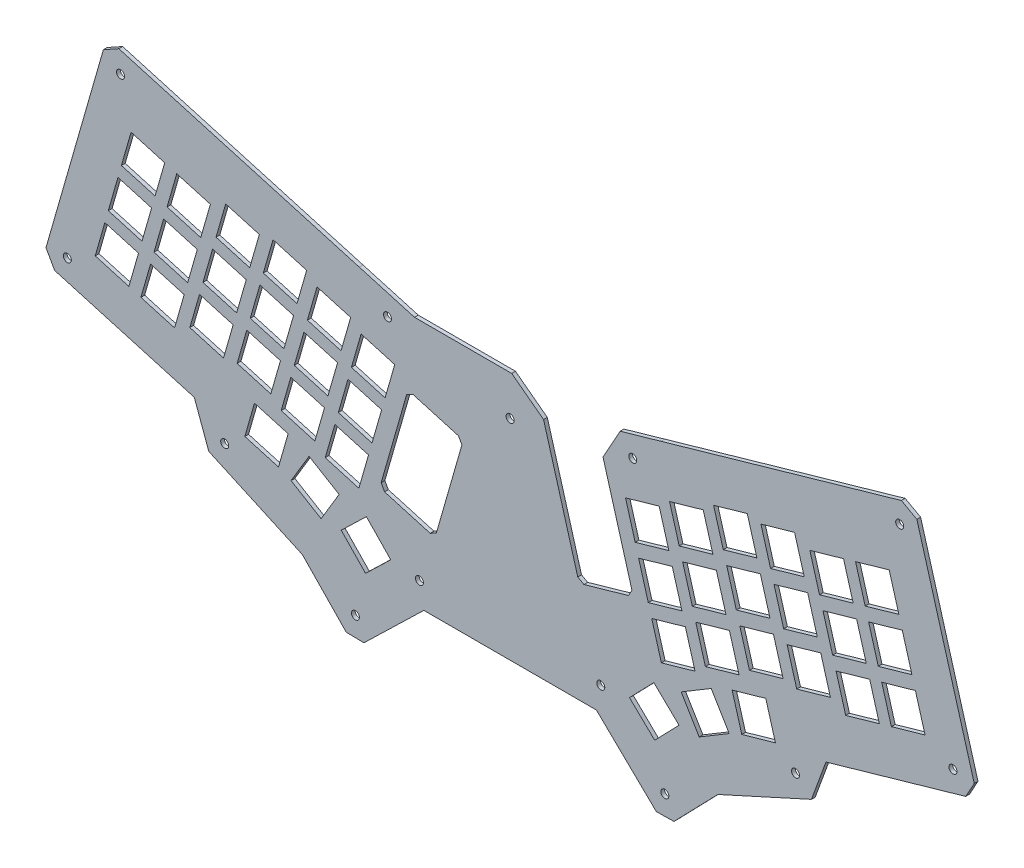
SolidWorks part; units mm, degrees
ref_plane "Plan de face" through (0, 0, 0) normal (0, 0, 1) x (1, 0, 0)
ref_plane "Plan de dessus" through (0, 0, 0) normal (0, 1, 0) x (1, 0, 0)
ref_plane "Plan de droite" through (0, 0, 0) normal (1, 0, 0) x (0, 0, -1)
sketch "Esquisse1" plane through (0, 0, 0) normal (0, 0, 1) x (1, 0, 0)
  line L0 (-121.6461, -32.0475) -> (-108.1875, -28.1884)
  line L1 (-108.1875, -28.1884) -> (-104.3283, -41.647)
  line L2 (-104.3283, -41.647) -> (-117.7869, -45.5062)
  line L3 (-117.7869, -45.5062) -> (-121.6461, -32.0475)
  line L4 (-100.1763, -37.9855) -> (-104.0355, -24.5269)
  line L5 (-104.0355, -24.5269) -> (-90.5769, -20.6677)
  line L6 (-90.5769, -20.6677) -> (-86.7177, -34.1263)
  line L7 (-86.7177, -34.1263) -> (-100.1763, -37.9855)
  line L8 (-82.5657, -30.4649) -> (-86.4249, -17.0063)
  line L9 (-86.4249, -17.0063) -> (-72.9663, -13.1471)
  line L10 (-72.9663, -13.1471) -> (-69.1071, -26.6057)
  line L11 (-69.1071, -26.6057) -> (-82.5657, -30.4649)
  line L12 (-63.6458, -27.5106) -> (-67.505, -14.0519)
  line L13 (-67.505, -14.0519) -> (-54.0463, -10.1927)
  line L14 (-54.0463, -10.1927) -> (-50.1872, -23.6514)
  line L15 (-50.1872, -23.6514) -> (-63.6458, -27.5106)
  line L16 (-44.0711, -26.8394) -> (-47.9303, -13.3808)
  line L17 (-47.9303, -13.3808) -> (-34.4717, -9.5216)
  line L18 (-34.4717, -9.5216) -> (-30.6125, -22.9802)
  line L19 (-30.6125, -22.9802) -> (-44.0711, -26.8394)
  line L20 (-25.8054, -21.6018) -> (-29.6646, -8.1432)
  line L21 (-29.6646, -8.1432) -> (-16.206, -4.284)
  line L22 (-16.206, -4.284) -> (-12.3468, -17.7426)
  line L23 (-12.3468, -17.7426) -> (-25.8054, -21.6018)
  line L24 (-116.4086, -50.3128) -> (-102.95, -46.4536)
  line L25 (-102.95, -46.4536) -> (-99.0908, -59.9122)
  line L26 (-99.0908, -59.9122) -> (-112.5494, -63.7714)
  line L27 (-112.5494, -63.7714) -> (-116.4086, -50.3128)
  line L28 (-98.798, -42.7922) -> (-85.3394, -38.933)
  line L29 (-85.3394, -38.933) -> (-81.4802, -52.3916)
  line L30 (-81.4802, -52.3916) -> (-94.9388, -56.2508)
  line L31 (-94.9388, -56.2508) -> (-98.798, -42.7922)
  line L32 (-81.1874, -35.2715) -> (-67.7288, -31.4123)
  line L33 (-67.7288, -31.4123) -> (-63.8696, -44.8709)
  line L34 (-63.8696, -44.8709) -> (-77.3282, -48.7301)
  line L35 (-77.3282, -48.7301) -> (-81.1874, -35.2715)
  line L36 (-62.2675, -32.3172) -> (-48.8089, -28.458)
  line L37 (-48.8089, -28.458) -> (-44.9497, -41.9166)
  line L38 (-44.9497, -41.9166) -> (-58.4083, -45.7758)
  line L39 (-58.4083, -45.7758) -> (-62.2675, -32.3172)
  line L40 (-42.6928, -31.646) -> (-29.2342, -27.7869)
  line L41 (-29.2342, -27.7869) -> (-25.375, -41.2455)
  line L42 (-25.375, -41.2455) -> (-38.8336, -45.1047)
  line L43 (-38.8336, -45.1047) -> (-42.6928, -31.646)
  line L44 (-24.4271, -26.4084) -> (-10.9685, -22.5492)
  line L45 (-10.9685, -22.5492) -> (-7.1093, -36.0078)
  line L46 (-7.1093, -36.0078) -> (-20.5679, -39.867)
  line L47 (-20.5679, -39.867) -> (-24.4271, -26.4084)
  line L48 (-19.1896, -44.6737) -> (-5.731, -40.8145)
  line L49 (-5.731, -40.8145) -> (-1.8718, -54.2731)
  line L50 (-1.8718, -54.2731) -> (-15.3304, -58.1323)
  line L51 (-15.3304, -58.1323) -> (-19.1896, -44.6737)
  line L52 (-37.4554, -49.9113) -> (-23.9967, -46.0521)
  line L53 (-23.9967, -46.0521) -> (-20.1376, -59.5107)
  line L54 (-20.1376, -59.5107) -> (-33.5962, -63.3699)
  line L55 (-33.5962, -63.3699) -> (-37.4554, -49.9113)
  line L56 (-57.03, -50.5825) -> (-43.5714, -46.7233)
  line L57 (-43.5714, -46.7233) -> (-39.7122, -60.1819)
  line L58 (-39.7122, -60.1819) -> (-53.1708, -64.0411)
  line L59 (-53.1708, -64.0411) -> (-57.03, -50.5825)
  line L60 (-75.9499, -53.5368) -> (-62.4913, -49.6776)
  line L61 (-62.4913, -49.6776) -> (-58.6321, -63.1362)
  line L62 (-58.6321, -63.1362) -> (-72.0908, -66.9954)
  line L63 (-72.0908, -66.9954) -> (-75.9499, -53.5368)
  line L64 (-93.5605, -61.0574) -> (-80.1019, -57.1982)
  line L65 (-80.1019, -57.1982) -> (-76.2427, -70.6569)
  line L66 (-76.2427, -70.6569) -> (-89.7013, -74.516)
  line L67 (-89.7013, -74.516) -> (-93.5605, -61.0574)
  line L68 (-111.1711, -68.5781) -> (-97.7125, -64.7189)
  line L69 (-97.7125, -64.7189) -> (-93.8533, -78.1775)
  line L70 (-93.8533, -78.1775) -> (-107.3119, -82.0367)
  line L71 (-107.3119, -82.0367) -> (-111.1711, -68.5781)
  line L72 (-79.0181, -77.3048) -> (-65.5595, -73.4456)
  line L73 (-65.5595, -73.4456) -> (-61.7003, -86.9042)
  line L74 (-61.7003, -86.9042) -> (-75.1589, -90.7634)
  line L75 (-75.1589, -90.7634) -> (-79.0181, -77.3048)
  line L76 (-99.4001, -88.1351) -> (-87.3916, -80.9362)
  line L77 (-87.3916, -80.9362) -> (-80.1927, -92.9448)
  line L78 (-80.1927, -92.9448) -> (-92.2012, -100.1436)
  line L79 (-92.2012, -100.1436) -> (-99.4001, -88.1351)
  line L80 (-120.0498, -100.4367) -> (-110.317, -90.3719)
  line L81 (-110.317, -90.3719) -> (-100.2522, -100.1047)
  line L82 (-100.2522, -100.1047) -> (-109.985, -110.1695)
  line L83 (-109.985, -110.1695) -> (-120.0498, -100.4367)
  line L86 (0.634, -55.7756) -> (-52.9527, -71.1413) construction
  line L89 (-59.2205, -88.2424) -> (-52.9527, -71.1413) construction
  line L96 (-93.4066, -103.0586) -> (-59.4637, -88.3612) construction
  line L97 (-105.418, -115.2057) -> (-93.9754, -103.3509) construction
  line L98 (-126.5332, -96.9919) -> (-107.5003, -115.385) construction
  line L100 (-106.3822, -25.4572) -> (-123.6848, -30.4187) construction
  line L101 (-72.1178, -10.6906) -> (-88.4663, -15.3784) construction
  line L102 (-53.2337, -7.6163) -> (-70.5393, -12.5786) construction
  line L103 (-33.6604, -6.9452) -> (-50.9661, -11.9075) construction
  line L104 (-15.3965, -1.7081) -> (-31.745, -6.396) construction
  line L105 (0.5403, -55.2132) -> (-14.6896, -2.0999) construction
  line L106 (-16.199, -60.6113) -> (0.1495, -55.9235) construction
  line L107 (-52.7198, -71.0835) -> (-18.1144, -61.1606) construction
  line L108 (-59.1184, -88.0534) -> (-52.9674, -71.2752) construction
  line L113 (-102.2678, -134.438) -> (-84.7238, -116.3191)
  line L114 (-84.7238, -116.3191) -> (-47.2969, -99.2981)
  line L115 (-47.2969, -99.2981) -> (-41.4917, -83.4594)
  line L116 (14.3812, -67.4381) -> (-41.4917, -83.4594)
  line L117 (17.8093, -61.2536) -> (-5.1371, 18.7701)
  line L122 (-11.3217, 22.1985) -> (-107.4545, -5.3614)
  line L129 (-167.7953, -27.6055) -> (-167.7953, -64.7189) construction
  line L130 (-242.0685, -103.8419) -> (-276.37, -88.2424) construction
  line L131 (-229.5108, -116.8112) -> (-242.0685, -103.8419) construction
  line L138 (-208.9328, -96.8551) -> (-229.5108, -116.8112) construction
  line L139 (-225.5107, -79.6567) -> (-208.9328, -96.8551) construction
  line L140 (-109.3352, -134.5492) -> (-102.2678, -134.438)
  line L142 (-5.1371, 18.7701) -> (-11.3217, 22.1985)
  line L143 (-211.4691, -30.6868) -> (-225.5107, -79.6567) construction
  line L147 (-114.18, -7.2899) -> (-107.4545, -5.3614)
  line L148 (-114.18, -7.2899) -> (-123.7936, -10.0465)
  line L154 (-4.3102, 15.8863) -> (-127.3606, -19.3904) construction
  line L155 (-131.531, -101.8802) -> (-105.9239, -126.7133) construction
  line L156 (-105.9239, -126.7133) -> (-89.4162, -109.6646) construction
  line L157 (-127.3539, -97.573) -> (-106.0575, -118.2258) construction
  line L158 (-106.0575, -118.2258) -> (-92.9354, -104.6737) construction
  line L159 (-92.9354, -104.6737) -> (-58.4256, -88.9794) construction
  line L160 (-58.4256, -88.9794) -> (-52.1886, -71.9625) construction
  line L161 (1.8709, -56.4612) -> (-52.1886, -71.9625) construction
  line L162 (1.8709, -56.4612) -> (-14.1861, -0.4639) construction
  line L163 (-14.1861, -0.4639) -> (-50.7166, -10.9388) construction
  line L164 (-50.7166, -10.9388) -> (-52.026, -6.3725) construction
  line L165 (-52.026, -6.3725) -> (-70.2913, -11.61) construction
  line L166 (-70.2913, -11.61) -> (-70.911, -9.4488) construction
  line L167 (-70.911, -9.4488) -> (-90.1377, -14.9608) construction
  line L168 (-90.1377, -14.9608) -> (-89.5177, -17.1231) construction
  line L169 (-89.5177, -17.1231) -> (-107.783, -22.3606) construction
  line L170 (-107.783, -22.3606) -> (-107.0938, -24.7639) construction
  line L171 (-107.0938, -24.7639) -> (-125.3583, -30.0011) construction
  line L172 (-125.3583, -30.0011) -> (-111.0411, -79.9324) construction
  line L173 (-110.7998, -78.9627) -> (-127.3777, -96.1611) construction
  line L174 (-89.4162, -109.6646) -> (-53.6562, -93.4017) construction
  line L175 (-53.6562, -93.4017) -> (-47.6042, -76.8897) construction
  line L176 (9.2923, -60.5749) -> (-47.6042, -76.8897) construction
  line L177 (9.2923, -60.5749) -> (-12.0005, 13.6817) construction
  line L178 (-229.7336, -25.4495) -> (-211.4691, -30.6868) construction
  line L179 (-229.0444, -23.0462) -> (-229.7336, -25.4495) construction
  line L181 (-247.3097, -17.8087) -> (-229.0444, -23.0462) construction
  line L185 (17.8093, -61.2536) -> (14.3812, -67.4381)
  line L190 (-246.6897, -15.6465) -> (-247.3097, -17.8087) construction
  line L191 (-263.9939, -10.6857) -> (-246.6897, -15.6465) construction
  line L192 (-264.6136, -12.8469) -> (-263.9939, -10.6857) construction
  line L193 (-282.8789, -7.6094) -> (-264.6136, -12.8469) construction
  line L194 (-284.1883, -12.1757) -> (-282.8789, -7.6094) construction
  line L195 (-320.7188, -1.7008) -> (-284.1883, -12.1757) construction
  line L196 (-336.2245, -55.7756) -> (-320.7188, -1.7008) construction
  line L200 (-344.8828, -60.5749) -> (-323.5901, 13.6817) construction
  line L201 (-344.8828, -60.5749) -> (-287.9863, -76.8897) construction
  line L202 (-281.9343, -93.4017) -> (-287.9863, -76.8897) construction
  line L203 (-246.1743, -109.6646) -> (-281.9343, -93.4017) construction
  line L204 (-224.7907, -78.9627) -> (-208.2128, -96.1611) construction
  line L205 (-210.2322, -30.0011) -> (-224.5494, -79.9324) construction
  line L206 (-228.4967, -24.7639) -> (-210.2322, -30.0011) construction
  line L207 (-227.8075, -22.3606) -> (-228.4967, -24.7639) construction
  line L208 (-246.0728, -17.1231) -> (-227.8075, -22.3606) construction
  line L209 (-245.4528, -14.9608) -> (-246.0728, -17.1231) construction
  line L210 (-264.6796, -9.4488) -> (-245.4528, -14.9608) construction
  line L211 (-265.2993, -11.61) -> (-264.6796, -9.4488) construction
  line L212 (-283.5645, -6.3725) -> (-265.2993, -11.61) construction
  line L213 (-284.8739, -10.9388) -> (-283.5645, -6.3725) construction
  line L217 (0.634, -55.7756) -> (-14.8717, -1.7008) construction
  line L220 (-14.8717, -1.7008) -> (-51.4022, -12.1757) construction
  line L221 (-51.4022, -12.1757) -> (-52.7116, -7.6094) construction
  line L222 (-52.7116, -7.6094) -> (-70.9769, -12.8469) construction
  line L223 (-70.9769, -12.8469) -> (-71.5966, -10.6857) construction
  line L224 (-71.5966, -10.6857) -> (-88.9008, -15.6465) construction
  line L225 (-88.9008, -15.6465) -> (-88.2808, -17.8087) construction
  line L226 (-88.2808, -17.8087) -> (-106.5461, -23.0462) construction
  line L227 (-106.5461, -23.0462) -> (-105.8569, -25.4495) construction
  line L228 (-105.8569, -25.4495) -> (-124.1214, -30.6868) construction
  line L231 (-124.1214, -30.6868) -> (-110.0799, -79.6567) construction
  line L232 (-110.0799, -79.6567) -> (-126.6577, -96.8551) construction
  line L233 (-126.6577, -96.8551) -> (-106.0797, -116.8112) construction
  line L234 (-106.0797, -116.8112) -> (-93.522, -103.8419) construction
  line L235 (-93.522, -103.8419) -> (-59.2205, -88.2424) construction
  line L236 (-321.4044, -0.4639) -> (-284.8739, -10.9388) construction
  line L237 (-337.4614, -56.4612) -> (-321.4044, -0.4639) construction
  line L238 (-337.4614, -56.4612) -> (-283.4019, -71.9625) construction
  line L239 (-277.1649, -88.9794) -> (-283.4019, -71.9625) construction
  line L240 (-242.6551, -104.6737) -> (-277.1649, -88.9794) construction
  line L241 (-229.5331, -118.2258) -> (-242.6551, -104.6737) construction
  line L242 (-208.2366, -97.573) -> (-229.5331, -118.2258) construction
  line L243 (-229.6666, -126.7133) -> (-246.1743, -109.6646) construction
  line L244 (-204.0596, -101.8802) -> (-229.6666, -126.7133) construction
  line L245 (-331.2803, 15.8863) -> (-208.2299, -19.3904) construction
  line L251 (-276.4721, -88.0534) -> (-282.6232, -71.2752) construction
  line L252 (-282.8707, -71.0835) -> (-317.4761, -61.1606) construction
  line L253 (-319.3915, -60.6113) -> (-335.74, -55.9235) construction
  line L254 (-336.1309, -55.2132) -> (-320.9009, -2.0999) construction
  line L255 (-320.194, -1.7081) -> (-303.8455, -6.396) construction
  line L256 (-301.9301, -6.9452) -> (-284.6245, -11.9075) construction
  line L257 (-282.3568, -7.6163) -> (-265.0512, -12.5786) construction
  line L258 (-263.4727, -10.6906) -> (-247.1242, -15.3784) construction
  line L259 (-229.2083, -25.4572) -> (-211.9057, -30.4187) construction
  line L261 (-209.0573, -96.9919) -> (-228.0902, -115.385) construction
  line L262 (-230.1725, -115.2057) -> (-241.6151, -103.3509) construction
  line L263 (-242.1839, -103.0586) -> (-276.1268, -88.3612) construction
  line L264 (-276.37, -88.2424) -> (-282.6379, -71.1413) construction
  line L265 (-336.2245, -55.7756) -> (-282.6379, -71.1413) construction
  line L268 (-353.3998, -61.2536) -> (-349.9717, -67.4381)
  line L274 (-221.4105, -7.2899) -> (-206.0252, -11.7015)
  line L275 (-221.4105, -7.2899) -> (-228.136, -5.3614)
  line L276 (-330.4534, 18.7701) -> (-324.2688, 22.1985)
  line L277 (-226.2553, -134.5492) -> (-233.3227, -134.438)
  line L281 (-324.2688, 22.1985) -> (-228.136, -5.3614)
  line L282 (-353.3998, -61.2536) -> (-330.4534, 18.7701)
  line L283 (-349.9717, -67.4381) -> (-294.0988, -83.4594)
  line L284 (-288.2936, -99.2981) -> (-294.0988, -83.4594)
  line L285 (-250.8667, -116.3191) -> (-288.2936, -99.2981)
  line L286 (-233.3227, -134.438) -> (-250.8667, -116.3191)
  line L288 (-225.6055, -110.1695) -> (-215.5407, -100.4367)
  line L289 (-235.3383, -100.1047) -> (-225.6055, -110.1695)
  line L290 (-225.2735, -90.3719) -> (-235.3383, -100.1047)
  line L291 (-215.5407, -100.4367) -> (-225.2735, -90.3719)
  line L292 (-243.3893, -100.1436) -> (-236.1904, -88.1351)
  line L293 (-255.3978, -92.9448) -> (-243.3893, -100.1436)
  line L294 (-248.1989, -80.9362) -> (-255.3978, -92.9448)
  line L295 (-236.1904, -88.1351) -> (-248.1989, -80.9362)
  line L296 (-260.4316, -90.7634) -> (-256.5724, -77.3048)
  line L297 (-273.8902, -86.9042) -> (-260.4316, -90.7634)
  line L298 (-270.031, -73.4456) -> (-273.8902, -86.9042)
  line L299 (-256.5724, -77.3048) -> (-270.031, -73.4456)
  line L300 (-228.2786, -82.0367) -> (-224.4194, -68.5781)
  line L301 (-241.7372, -78.1775) -> (-228.2786, -82.0367)
  line L302 (-237.878, -64.7189) -> (-241.7372, -78.1775)
  line L303 (-224.4194, -68.5781) -> (-237.878, -64.7189)
  line L304 (-245.8892, -74.516) -> (-242.03, -61.0574)
  line L305 (-259.3478, -70.6569) -> (-245.8892, -74.516)
  line L306 (-255.4886, -57.1982) -> (-259.3478, -70.6569)
  line L307 (-242.03, -61.0574) -> (-255.4886, -57.1982)
  line L308 (-263.4998, -66.9954) -> (-259.6406, -53.5368)
  line L309 (-276.9584, -63.1362) -> (-263.4998, -66.9954)
  line L310 (-273.0992, -49.6776) -> (-276.9584, -63.1362)
  line L311 (-259.6406, -53.5368) -> (-273.0992, -49.6776)
  line L312 (-282.4197, -64.0411) -> (-278.5605, -50.5825)
  line L313 (-295.8783, -60.1819) -> (-282.4197, -64.0411)
  line L314 (-292.0191, -46.7233) -> (-295.8783, -60.1819)
  line L315 (-278.5605, -50.5825) -> (-292.0191, -46.7233)
  line L316 (-301.9944, -63.3699) -> (-298.1352, -49.9113)
  line L317 (-315.453, -59.5107) -> (-301.9944, -63.3699)
  line L318 (-311.5938, -46.0521) -> (-315.453, -59.5107)
  line L319 (-298.1352, -49.9113) -> (-311.5938, -46.0521)
  line L320 (-320.2601, -58.1323) -> (-316.4009, -44.6737)
  line L321 (-333.7187, -54.2731) -> (-320.2601, -58.1323)
  line L322 (-329.8595, -40.8145) -> (-333.7187, -54.2731)
  line L323 (-316.4009, -44.6737) -> (-329.8595, -40.8145)
  line L324 (-315.0226, -39.867) -> (-311.1634, -26.4084)
  line L325 (-328.4812, -36.0078) -> (-315.0226, -39.867)
  line L326 (-324.622, -22.5492) -> (-328.4812, -36.0078)
  line L327 (-311.1634, -26.4084) -> (-324.622, -22.5492)
  line L328 (-296.7569, -45.1047) -> (-292.8977, -31.646)
  line L329 (-310.2155, -41.2455) -> (-296.7569, -45.1047)
  line L330 (-306.3563, -27.7869) -> (-310.2155, -41.2455)
  line L331 (-292.8977, -31.646) -> (-306.3563, -27.7869)
  line L332 (-277.1822, -45.7758) -> (-273.323, -32.3172)
  line L333 (-290.6408, -41.9166) -> (-277.1822, -45.7758)
  line L334 (-286.7817, -28.458) -> (-290.6408, -41.9166)
  line L335 (-273.323, -32.3172) -> (-286.7817, -28.458)
  line L336 (-258.2623, -48.7301) -> (-254.4031, -35.2715)
  line L337 (-271.7209, -44.8709) -> (-258.2623, -48.7301)
  line L338 (-267.8617, -31.4123) -> (-271.7209, -44.8709)
  line L339 (-254.4031, -35.2715) -> (-267.8617, -31.4123)
  line L340 (-240.6517, -56.2508) -> (-236.7925, -42.7922)
  line L341 (-254.1103, -52.3916) -> (-240.6517, -56.2508)
  line L342 (-250.2511, -38.933) -> (-254.1103, -52.3916)
  line L343 (-236.7925, -42.7922) -> (-250.2511, -38.933)
  line L344 (-223.0411, -63.7714) -> (-219.1819, -50.3128)
  line L345 (-236.4997, -59.9122) -> (-223.0411, -63.7714)
  line L346 (-232.6405, -46.4536) -> (-236.4997, -59.9122)
  line L347 (-219.1819, -50.3128) -> (-232.6405, -46.4536)
  line L348 (-323.2438, -17.7426) -> (-309.7851, -21.6018)
  line L349 (-319.3846, -4.284) -> (-323.2438, -17.7426)
  line L350 (-305.926, -8.1432) -> (-319.3846, -4.284)
  line L351 (-309.7851, -21.6018) -> (-305.926, -8.1432)
  line L352 (-304.978, -22.9802) -> (-291.5194, -26.8394)
  line L353 (-301.1188, -9.5216) -> (-304.978, -22.9802)
  line L354 (-287.6602, -13.3808) -> (-301.1188, -9.5216)
  line L355 (-291.5194, -26.8394) -> (-287.6602, -13.3808)
  line L356 (-285.4034, -23.6514) -> (-271.9448, -27.5106)
  line L357 (-281.5442, -10.1927) -> (-285.4034, -23.6514)
  line L358 (-268.0856, -14.0519) -> (-281.5442, -10.1927)
  line L359 (-271.9448, -27.5106) -> (-268.0856, -14.0519)
  line L360 (-266.4834, -26.6057) -> (-253.0248, -30.4649)
  line L361 (-262.6242, -13.1471) -> (-266.4834, -26.6057)
  line L362 (-249.1656, -17.0063) -> (-262.6242, -13.1471)
  line L363 (-253.0248, -30.4649) -> (-249.1656, -17.0063)
  line L364 (-248.8728, -34.1263) -> (-235.4142, -37.9855)
  line L365 (-245.0136, -20.6677) -> (-248.8728, -34.1263)
  line L366 (-231.555, -24.5269) -> (-245.0136, -20.6677)
  line L367 (-235.4142, -37.9855) -> (-231.555, -24.5269)
  line L368 (-217.8036, -45.5062) -> (-213.9444, -32.0475)
  line L369 (-231.2622, -41.647) -> (-217.8036, -45.5062)
  line L370 (-227.4031, -28.1884) -> (-231.2622, -41.647)
  line L371 (-213.9444, -32.0475) -> (-227.4031, -28.1884)
  line L372 (-226.2553, -134.5492) -> (-202.2968, -111.3509)
  line L373 (-109.3352, -134.5492) -> (-133.2937, -111.3509)
  line L374 (-141.5559, -103.3509) -> (-194.0347, -103.3509) construction
  line L389 (-206.0252, -11.7015) -> (-129.5654, -11.7015) construction
  line L390 (-119.0708, -62.7964) -> (-130.6498, -22.4155)
  line L391 (-123.5545, -47.16) -> (-127.4136, -33.7014) construction
  line L392 (-120.442, -65.2702) -> (-138.2688, -70.3819)
  line L393 (-140.7426, -69.0107) -> (-154.4194, -21.3141)
  line L394 (-167.1758, -11.7015) -> (-206.0252, -11.7015)
  line L395 (-154.4194, -21.3141) -> (-167.1758, -11.7015)
  line L396 (-123.7936, -10.0465) -> (-130.6498, -22.4155)
  line L397 (-138.2688, -70.3819) -> (-140.7426, -69.0107)
  line L398 (-119.0708, -62.7964) -> (-120.442, -65.2702)
  line L399 (-129.5654, -11.7015) -> (-123.7936, -10.0465) construction
  line L400 (-133.2937, -111.3509) -> (-202.2968, -111.3509)
  line L401 (-141.5559, -111.3509) -> (-194.0347, -111.3509) construction
  line L402 (-197.2749, -82.0103) -> (-187.0783, -46.443)
  line L403 (-188.4497, -43.9693) -> (-206.714, -38.7332)
  line L404 (-219.3843, -75.6719) -> (-209.1877, -40.1046)
  line L405 (-199.7487, -83.3817) -> (-218.0129, -78.1456)
  line L406 (-206.714, -38.7332) -> (-209.1877, -40.1046)
  line L407 (-187.0783, -46.443) -> (-188.4497, -43.9693)
  line L408 (-199.7487, -83.3817) -> (-197.2749, -82.0103)
  line L409 (-218.0129, -78.1456) -> (-219.3843, -75.6719)
  line L410 (-192.1766, -64.2267) -> (-167.7953, -64.7189) construction
  circle A2 centre (-12.0005, 13.6817) radius 1.6
  circle A3 centre (-12.0005, 13.6817) radius 3 construction
  circle A4 centre (-118.7579, -16.9241) radius 1.6
  circle A5 centre (9.2923, -60.5749) radius 1.6
  circle A6 centre (-53.6562, -93.4017) radius 1.6
  circle A7 centre (-105.9239, -126.7133) radius 1.6
  circle A8 centre (-131.531, -101.8802) radius 1.6
  circle A10 centre (-147.4897, -45.973) radius 1.6 construction
  circle A11 centre (-323.5901, 13.6817) radius 3 construction
  circle A12 centre (-188.1008, -45.973) radius 1.6 construction
  circle A14 centre (-204.0596, -101.8802) radius 1.6
  circle A15 centre (-229.6666, -126.7133) radius 1.6
  circle A16 centre (-281.9343, -93.4017) radius 1.6
  circle A17 centre (-344.8828, -60.5749) radius 1.6
  circle A18 centre (-216.8326, -16.9241) radius 1.6
  circle A19 centre (-323.5901, 13.6817) radius 1.6
  circle A20 centre (-167.7953, -27.6055) radius 1.6
  point P138 (-167.7953, -27.6055)
  point P139 (-6.5153, 23.5764)
  point P150 (-169.1046, -23.0392)
  point P200 (19.1875, -66.0599)
  point P203 (-141.5228, -71.3355)
  point P204 (-141.5228, 1.5705)
  point P263 (-133.4062, -12.8029)
  point P264 (-118.5195, -64.7189)
  point P283 (-140.1914, -70.9332)
  point P284 (-157.1758, -11.7015)
  point P405 (-354.778, -66.0599)
  point P406 (-329.0752, 23.5764)
  dimension "D3" = 3.2
  dimension "D4" = 6
  dimension "D6" = 3.2
  dimension "D7" = 3.2
  dimension "D8" = 3.2
  dimension "D9" = 3.2
  dimension "D10" = 3.2
  dimension "D16" = 3.2
  dimension "D2" = 6
  dimension "D5" = 8
extrude "Boss.-Extru.1" add sketch "Esquisse1" along normal blind 1.5
